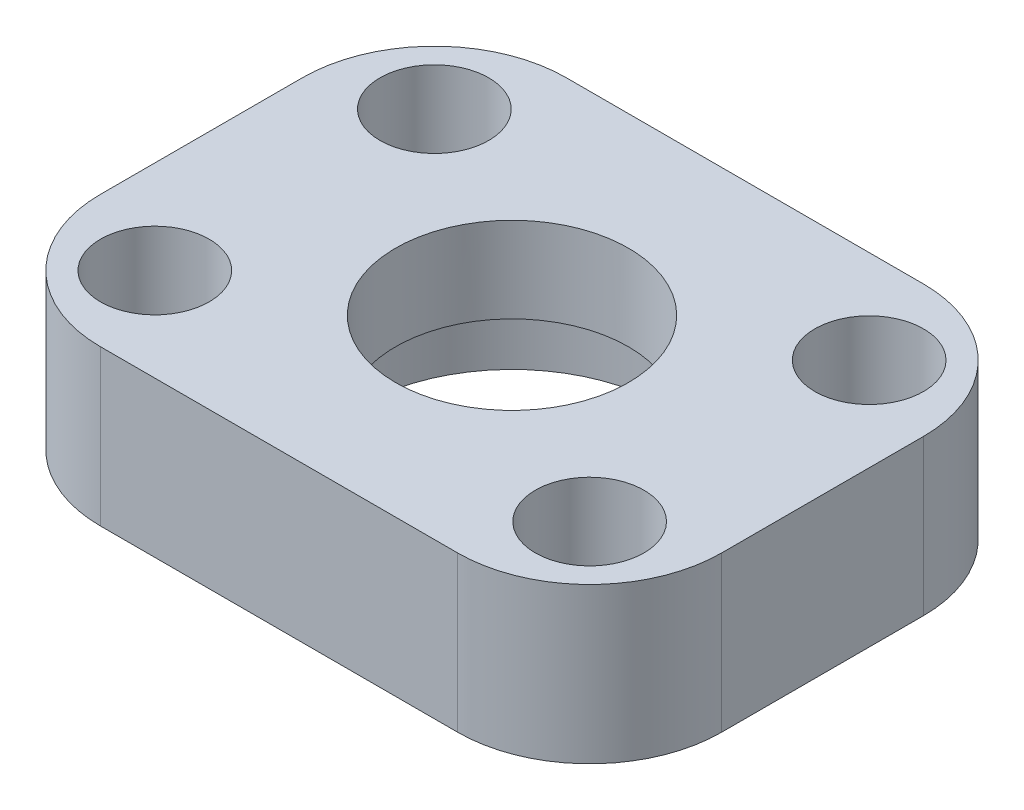
SolidWorks part; units mm, degrees
ref_plane "Front Plane" through (0, 0, 0) normal (0, 0, 1) x (1, 0, 0)
ref_plane "Top Plane" through (0, 0, 0) normal (0, 1, 0) x (1, 0, 0)
ref_plane "Right Plane" through (0, 0, 0) normal (1, 0, 0) x (0, 0, -1)
sketch "Sketch1" plane through (0, 0, 0) normal (0, 1, 0) x (1, 0, 0)
  line L1 (-20, 15) -> (20, 15)
  line L2 (-20, 15) -> (-20, -15)
  line L3 (-20, -15) -> (20, -15)
  line L4 (20, 15) -> (20, -15)
  line L5 (-20, 15) -> (20, -15) construction
  line L6 (-20, -15) -> (20, 15) construction
  point P0 (0, 0)
  dimension "D1" = 30
  dimension "D2" = 40
extrude "Boss-Extrude1" add sketch "Sketch1" along normal blind 10
sketch "Sketch3" plane through (0, 0, 0) normal (0, -1, 0) x (1, 0, 0)
  circle A0 centre (0, 0) radius 9.875
  dimension "D1" = 19.75
extrude "Cut-Extrude1" cut sketch "Sketch3" against normal blind 4.5
sketch "Sketch4" plane through (0, 10, 0) normal (0, 1, 0) x (1, 0, 0)
  circle A0 centre (0, 0) radius 7.5
  dimension "D1" = 15
extrude "Cut-Extrude2" cut sketch "Sketch4" against normal through all
hole_wizard "Ø3.0mm Dowel Hole1" positions "Sketch7" profile "Sketch8" hole size "Ø3.0" standard "ANSI Metric" end condition up to next
sketch "Sketch7" plane through (0, 10, 0) normal (0, 1, 0) x (1, 0, 0)
  line L0 (20, 0) -> (-20, 0) construction
  line L1 (20, -15) -> (20, 15) construction
  line L2 (-20, 15) -> (-20, -15) construction
  line L4 (0, 15) -> (0, -15) construction
  line L5 (20, 15) -> (-20, 15) construction
  line L6 (-20, -15) -> (20, -15) construction
  point P0 (-14, 9)
  point P21 (-14, -9)
  point P22 (14, -9)
  point P23 (14, 9)
  dimension "D1" = 6
  dimension "D2" = 6
sketch "Sketch8" plane through (-14, 10, -9) normal (1, 0, 0) x (0, 0, 1)
  line L0 (0, 0) -> (0, 10)
  line L1 (0, 10) -> (1.5, 10)
  line L2 (1.5, 10) -> (1.5, 0)
  line L5 (1.5, 0) -> (0, 0)
  line L11 (0, -6.35) -> (0, 107.95) construction
  dimension "Thru Hole Dia." = 3
  dimension "Thru Hole Depth" = 10
fillet "Fillet1" radius 8.5 4 edges at (20, 5, -15) (20, 5, 15) (-20, 5, 15) (-20, 5, -15)
sketch "Sketch9" plane through (0, 10, 0) normal (0, 1, 0) x (1, 0, 0)
  line L0 (14, -9) -> (-14, -9) construction
  circle A0 centre (14, -9) radius 3.5
  circle A1 centre (-14, -9) radius 3.5
  circle A2 centre (-14, 9) radius 3.5
  circle A3 centre (14, 9) radius 3.5
  dimension "D1" = 7
  dimension "D4" = 28
  dimension "D5" = 18
  dimension "D2" = 2
  dimension "D3" = 2
extrude "Cut-Extrude3" cut sketch "Sketch9" against normal blind 5
